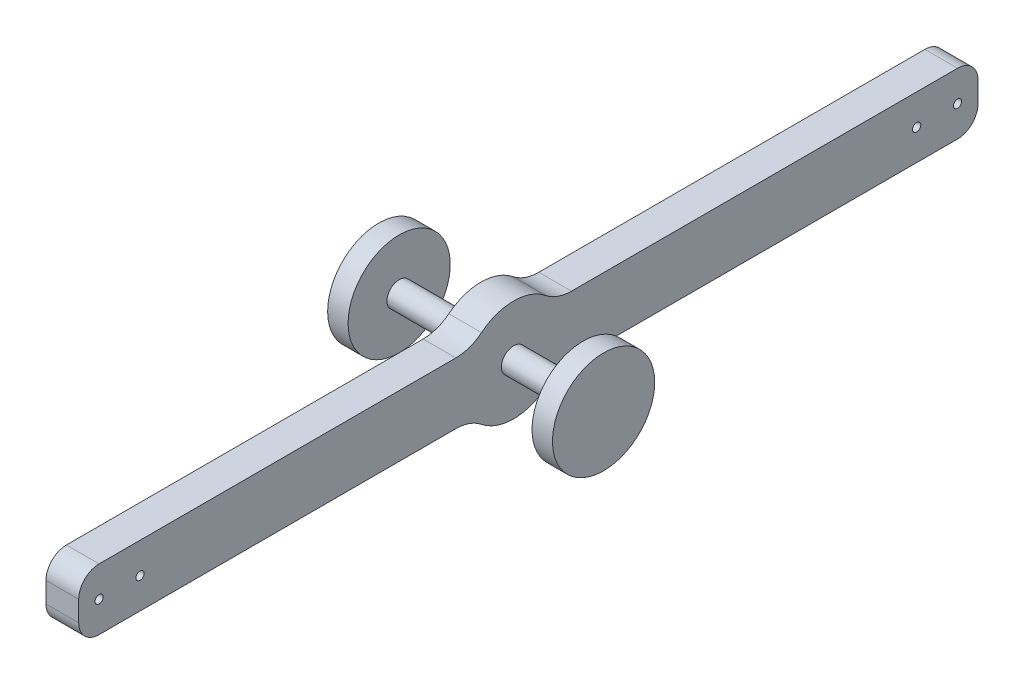
SolidWorks part; units mm, degrees
ref_plane "前视基准面" through (0, 0, 0) normal (0, 0, 1) x (1, 0, 0)
ref_plane "上视基准面" through (0, 0, 0) normal (0, 1, 0) x (1, 0, 0)
ref_plane "右视基准面" through (0, 0, 0) normal (1, 0, 0) x (0, 0, -1)
other "Configuration Table"
sketch "草图1" plane through (0, 0, 0) normal (1, 0, 0) x (0, 0, -1)
  line L1 (0, 0) -> (120, 0)
  line L2 (0, 0) -> (0, 15)
  line L3 (0, 15) -> (120, 15)
  line L4 (120, 0) -> (120, 15)
  dimension "D1" = 15
  dimension "D2" = 120
extrude "凸台-拉伸1" add sketch "草图1" along normal blind 8
fillet "圆角1" radius 5 4 edges at (4, 0, -120) (4, 15, -120) (4, 0, 0) (4, 15, 0)
sketch "草图6" plane through (8, 0, 0) normal (1, 0, 0) x (0, 0, -1)
  circle A0 centre (6.4, 7.5) radius 12.5
extrude "凸台-拉伸2" add sketch "草图6" against normal up to surface (8 mm away) up to face at (0, 7.5, -60)
sketch "草图9" plane through (0, 0, 0) normal (0, 0, 1) x (1, 0, 0)
  line L0 (0, 20) -> (0, -5) construction
  line L1 (0, 15) -> (8, 15)
  line L2 (0, 15) -> (0, 0)
  line L3 (0, 0) -> (8, 0)
  line L4 (8, 15) -> (8, 0)
  line L5 (2.5, 7.5) -> (0, 7.5) construction
  dimension "D1" = 15
  dimension "D2" = 7.5
  dimension "D3" = 8
extrude "凸台-拉伸3" add sketch "草图9" along normal blind 100
fillet "圆角2" radius 10 4 edges at (4, 15, -16.4) (4, 0, -16.4) (4, 0, 3.6) (4, 15, 3.6)
fillet "圆角4" radius 5 2 edges at (4, 0, 100) (4, 15, 100)
sketch "草图11" plane through (0, 0, 0) normal (-1, 0, 0) x (0, 0, 1)
  line L0 (-120, 7.5) -> (-91.0607, 7.5) construction
  line L1 (-120, 5) -> (-120, 10) construction
  line L2 (100, 7.5) -> (83.7402, 7.5) construction
  line L3 (100, 10) -> (100, 5) construction
  circle A0 centre (-115, 7.5) radius 1
  circle A1 centre (-105, 7.5) radius 1
  circle A2 centre (85, 7.5) radius 1
  circle A3 centre (95, 7.5) radius 1
  dimension "D2" = 2
  dimension "D3" = 2
  dimension "D7" = 2
  dimension "D8" = 2
  dimension "D1" = 10
  dimension "D4" = 5
  dimension "D5" = 10
  dimension "D6" = 5
extrude "切除-拉伸8" cut sketch "草图11" against normal blind 10
sketch "草图15" plane through (0, 0, 0) normal (-1, 0, 0) x (0, 0, 1)
  line L0 (-6.4, 20) -> (-6.4, -5) construction
  arc A0 (1.4567, 17.2222) -> (-14.2567, 17.2222) centre (-6.4, 7.5) ccw construction
  arc A1 (-14.2567, -2.2222) -> (1.4567, -2.2222) centre (-6.4, 7.5) ccw construction
  circle A2 centre (-6.4, 7.5) radius 3
  dimension "D1" = 6
extrude "凸台-拉伸5" add sketch "草图15" along normal blind 20 and the other way blind 25
sketch "草图16" plane through (-20, 0, 0) normal (-1, 0, 0) x (0, 0, 1)
  line L0 (-6.4, 10.5) -> (-6.4, 4.5) construction
  circle A0 centre (-6.4, 7.5) radius 3 construction
  circle A1 centre (-6.4, 7.5) radius 3 construction
  circle A2 centre (-6.4, 7.5) radius 12.5
  dimension "D1" = 25
extrude "凸台-拉伸6" add sketch "草图16" along normal blind 5
sketch "草图17" plane through (25, 0, 0) normal (1, 0, 0) x (0, 0, -1)
  line L0 (6.4, 10.5) -> (6.4, 4.5) construction
  circle A0 centre (6.4, 7.5) radius 3 construction
  circle A1 centre (6.4, 7.5) radius 3 construction
  circle A2 centre (6.4, 7.5) radius 12.5
  dimension "D1" = 25
extrude "凸台-拉伸7" add sketch "草图17" along normal blind 5
